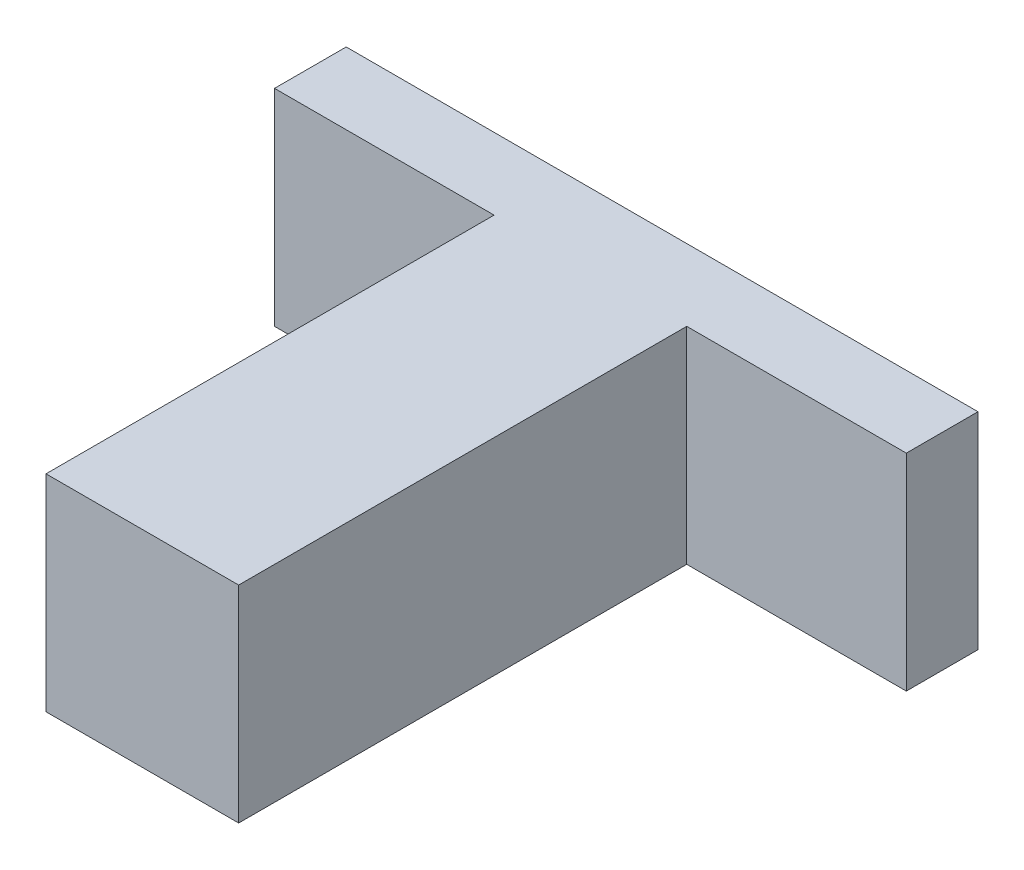
SolidWorks part; units mm, degrees
material "PLA"
ref_plane "Front Plane" through (0, 0, 0) normal (0, 0, 1) x (1, 0, 0)
ref_plane "Top Plane" through (0, 0, 0) normal (0, 1, 0) x (1, 0, 0)
ref_plane "Right Plane" through (0, 0, 0) normal (1, 0, 0) x (0, 0, -1)
sketch "Sketch1" plane through (0, 0, 0) normal (0, 1, 0) x (1, 0, 0)
  line L0 (0, 0) -> (14.1, 0)
  line L1 (14.1, 0) -> (14.1, -1.6)
  line L2 (14.1, -1.6) -> (9.2, -1.6)
  line L3 (9.2, -1.6) -> (9.2, -11.6)
  line L4 (9.2, -11.6) -> (4.9, -11.6)
  line L5 (4.9, -11.6) -> (4.9, -1.6)
  line L6 (4.9, -1.6) -> (0, -1.6)
  line L7 (0, -1.6) -> (0, 0)
  dimension "D1" = 1.6
  dimension "D2" = 14.1
  dimension "D3" = 4.3
  dimension "D4" = 10
extrude "Boss-Extrude1" add sketch "Sketch1" along normal blind 4.6
